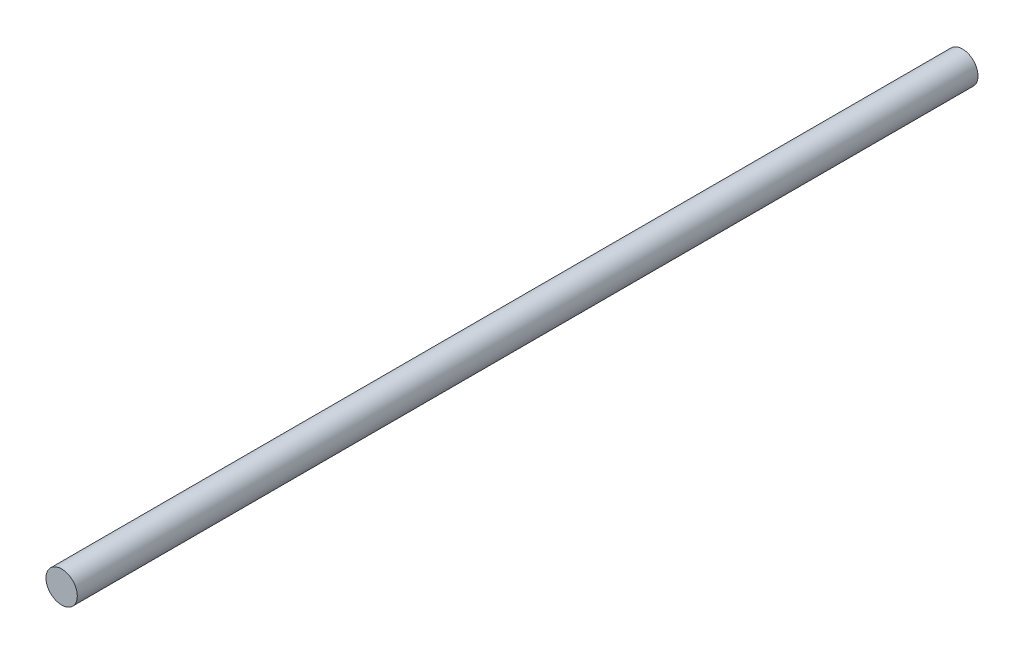
SolidWorks part; units mm, degrees
ref_plane "前视基准面" through (0, 0, 0) normal (0, 0, 1) x (1, 0, 0)
ref_plane "上视基准面" through (0, 0, 0) normal (0, 1, 0) x (1, 0, 0)
ref_plane "右视基准面" through (0, 0, 0) normal (1, 0, 0) x (0, 0, -1)
sketch "草图1" plane through (0, 0, 0) normal (0, 0, 1) x (1, 0, 0)
  circle A0 centre (0, 0) radius 2
extrude "凸台-拉伸1" add sketch "草图1" along normal blind 115
